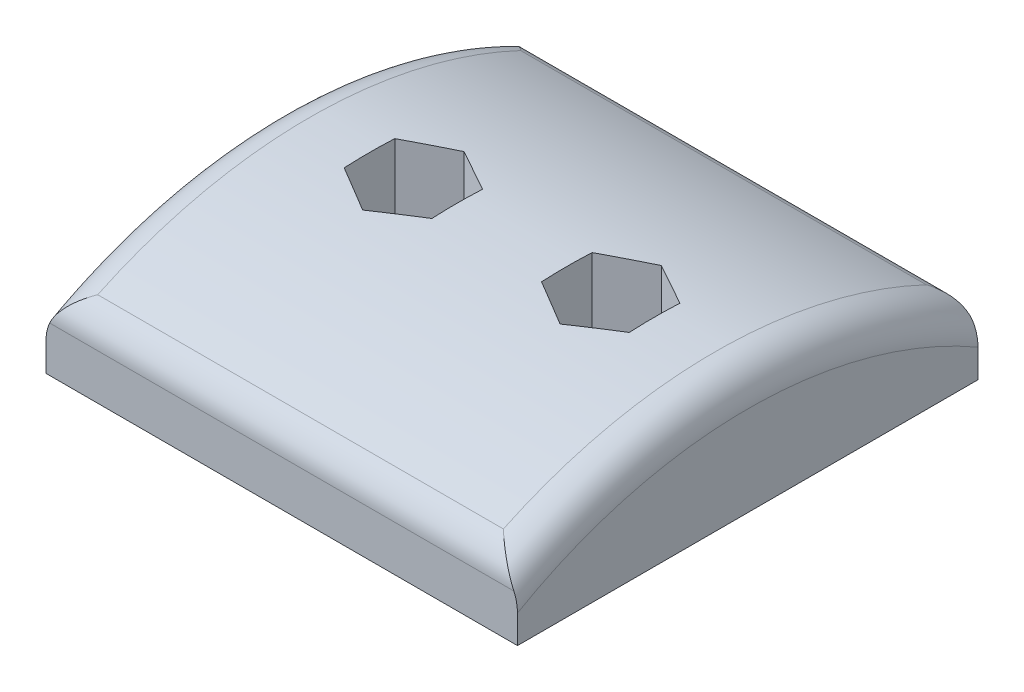
SolidWorks part; units mm, degrees
material "PE High Density"
ref_plane "Front Plane" through (0, 0, 0) normal (0, 0, 1) x (1, 0, 0)
ref_plane "Top Plane" through (0, 0, 0) normal (0, 1, 0) x (1, 0, 0)
ref_plane "Right Plane" through (0, 0, 0) normal (1, 0, 0) x (0, 0, -1)
sketch "Sketch2" plane through (0, 0, 0) normal (1, 0, 0) x (0, 0, -1)
  line L0 (-21, 6) -> (-21, 0)
  line L1 (-21, 0) -> (21, 0)
  line L2 (21, 0) -> (21, 6)
  arc A0 (-21, 6) -> (21, 6) centre (0, -33.7995) cw
  point P3 (0, 0)
  point P6 (0, 11.2005)
  dimension "D1" = 42
  dimension "D3" = 45
  dimension "D2" = 6
extrude "Boss-Extrude1" add sketch "Sketch2" along normal mid plane 43
fillet "Fillet1" radius 3 4 edges at (0, 6, -21) (21.5, 11.2005, 0) (0, 6, 21) (-21.5, 11.2005, 0)
sketch "Sketch3" plane through (0, 0, 0) normal (0, -1, 0) x (1, 0, 0)
  line L0 (9, 0) -> (0, 0) construction
  line L1 (5, 2.3094) -> (5, -2.3094)
  line L2 (5, -2.3094) -> (9, -4.6188)
  line L3 (9, -4.6188) -> (13, -2.3094)
  line L4 (13, -2.3094) -> (13, 2.3094)
  line L5 (13, 2.3094) -> (9, 4.6188)
  line L6 (9, 4.6188) -> (5, 2.3094)
  line L7 (0, 0) -> (0, -4.1487) construction
  line L8 (-9, 4.6188) -> (-5, 2.3094)
  line L9 (-13, 2.3094) -> (-9, 4.6188)
  line L10 (-13, -2.3094) -> (-13, 2.3094)
  line L11 (-9, -4.6188) -> (-13, -2.3094)
  line L12 (-5, -2.3094) -> (-9, -4.6188)
  line L13 (-5, 2.3094) -> (-5, -2.3094)
  circle A0 centre (9, 0) radius 4 construction
  point P17 (-9, 0)
  dimension "D1" = 18
  dimension "D2" = 8
extrude "Cut-Extrude1" cut sketch "Sketch3" against normal through all from offset 4 offset against normal yes
sketch "Sketch4" plane through (0, 0, 0) normal (0, -1, 0) x (1, 0, 0)
  circle A0 centre (9, 0) radius 2.5
  circle A1 centre (-9, 0) radius 2.5
  dimension "D1" = 5
extrude "Cut-Extrude2" cut sketch "Sketch4" against normal blind 4
